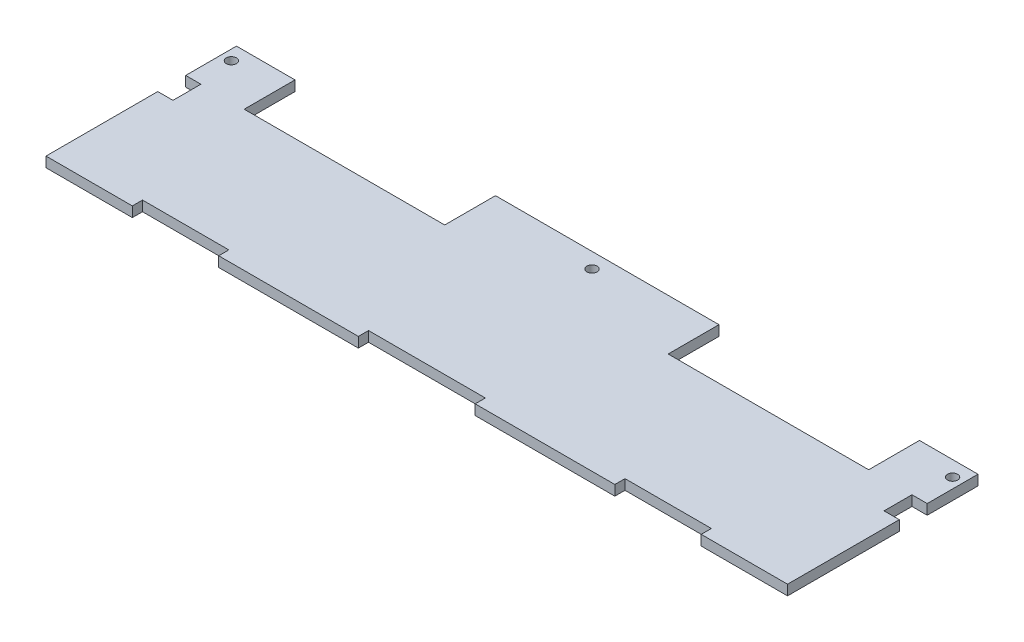
SolidWorks part; units mm, degrees
ref_plane "Front" through (0, 0, 0) normal (0, 0, 1) x (1, 0, 0)
ref_plane "Top" through (0, 0, 0) normal (0, 1, 0) x (1, 0, 0)
ref_plane "Right" through (0, 0, 0) normal (1, 0, 0) x (0, 0, -1)
sketch "Sketch1" plane through (0, 0, 0) normal (0, 1, 0) x (1, 0, 0)
  line L0 (-184.2498, 17.5) -> (170.2833, 17.5) construction
  line L1 (146, -37.5) -> (-146, -37.5)
  line L2 (146, -37.5) -> (146, 6.5)
  line L3 (146, 37.5) -> (122.95, 37.5)
  line L4 (-146, -37.5) -> (-146, 6.5)
  line L5 (146, -37.5) -> (-146, 37.5) construction
  line L6 (146, 37.5) -> (-146, -37.5) construction
  line L7 (-122.95, 37.5) -> (-122.95, 17.5)
  line L8 (-122.95, 17.5) -> (-44, 17.5)
  line L9 (-44, 17.5) -> (-44, 37.5)
  line L10 (44, 37.5) -> (44, 17.5)
  line L11 (122.95, 37.5) -> (122.95, 17.5)
  line L12 (-122.95, 37.5) -> (-146, 37.5)
  line L13 (44, 37.5) -> (-44, 37.5)
  line L14 (44, 17.5) -> (122.95, 17.5)
  line L15 (146, 17.5) -> (146, 37.5)
  line L16 (146, 17.5) -> (140, 17.5)
  line L17 (0, -37.5) -> (0, 0) construction
  line L18 (146, 6.5) -> (140, 6.5)
  line L19 (140, 17.5) -> (140, 6.5)
  line L20 (143, 6.5) -> (143, 17.5) construction
  line L21 (146, 12) -> (140, 12) construction
  line L22 (-146, 12) -> (-140, 12) construction
  line L23 (-143, 6.5) -> (-143, 17.5) construction
  line L24 (-140, 17.5) -> (-140, 6.5)
  line L25 (-146, 6.5) -> (-140, 6.5)
  line L26 (-146, 17.5) -> (-140, 17.5)
  line L27 (-146, 17.5) -> (-146, 37.5)
  circle A0 centre (-142, 31.5) radius 2
  circle A1 centre (142, 31.5) radius 2
  circle A2 centre (0, 31.5) radius 2
  point P0 (0, 0)
  point P36 (-143, 12)
  point P202 (143, 12)
  dimension "D6" = 4
  dimension "D10" = 4
  dimension "D12" = 4
  dimension "D1" = 292
  dimension "D2" = 75
  dimension "D3" = 20
  dimension "D4" = 44
  dimension "D5" = 44
  dimension "D7" = 23.05
  dimension "D8" = 23.05
  dimension "D9" = 4
  dimension "D11" = 4
  dimension "D13" = 11
  dimension "D14" = 6
  dimension "D15" = 6
extrude "Boss-Extrude1" add sketch "Sketch1" along normal blind 4
sketch "Sketch2" plane through (0, 4, 0) normal (0, 1, 0) x (1, 0, 0)
  line L0 (-112, -33.5) -> (-112, -37.5)
  line L1 (-78, -37.5) -> (-78, -33.5)
  line L2 (-78, -33.5) -> (-112, -33.5)
  line L3 (-23, -37.5) -> (-23, -33.5)
  line L4 (-23, -33.5) -> (23, -33.5)
  line L9 (23, -37.5) -> (23, -33.5)
  line L10 (78, -33.5) -> (112, -33.5)
  line L11 (78, -37.5) -> (78, -33.5)
  line L12 (112, -33.5) -> (112, -37.5)
  line L14 (-146, -37.5) -> (146, -37.5) construction
  line L15 (146, -37.5) -> (146, 6.5) construction
  line L17 (112, -37.5) -> (-112, -37.5) construction
  point P8 (-44.6457, -30.2407)
  point P19 (0, -33.5)
  point P24 (56.3543, -30.2407)
  line M17 (-146, -37.5) -> (146, -37.5)
  dimension "D1" = 34
  dimension "D2" = 4
  dimension "D3" = 55
  dimension "D4" = 46
  dimension "D5" = 55
  dimension "D7" = 34
  dimension "D8" = 34
extrude "Cut-Extrude1" cut sketch "Sketch2" against normal through all contours L12 L10 L11 M17 | L9 L4 L3 M17 | L1 L2 L0 M17
